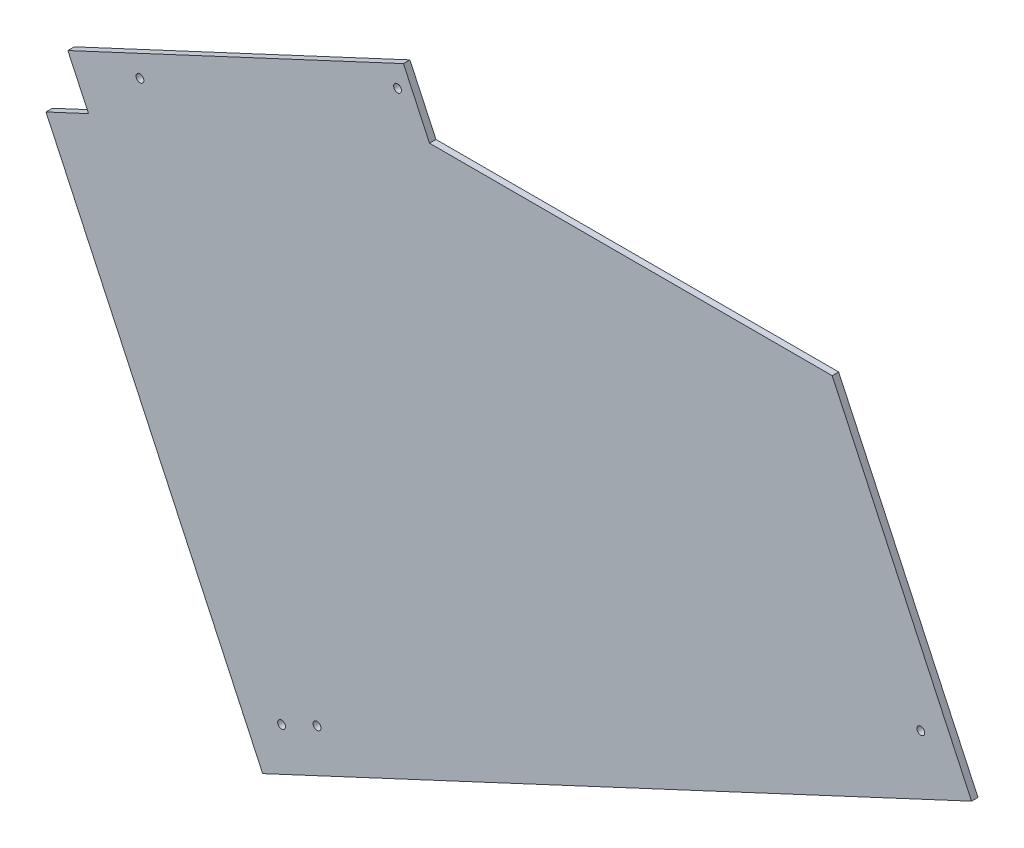
SolidWorks part; units mm, degrees
ref_plane "Front Plane" through (0, 0, 0) normal (0, 0, 1) x (1, 0, 0)
ref_plane "Top Plane" through (0, 0, 0) normal (0, 1, 0) x (1, 0, 0)
ref_plane "Right Plane" through (0, 0, 0) normal (1, 0, 0) x (0, 0, -1)
sketch "Sketch1" plane through (0, 0, 0) normal (0, 0, 1) x (1, 0, 0)
  line L0 (327.4362, 0.0035) -> (121.4984, 0.0035)
  line L1 (121.4984, 0.0035) -> (108.169, 28.5884)
  line L2 (108.169, 28.5884) -> (-63.4467, -51.4373)
  line L3 (-63.4467, -51.4373) -> (57.9293, -311.7289) construction
  line L4 (57.9293, -311.7289) -> (398.701, -152.8244)
  line L5 (271.5352, 119.8836) -> (277.3251, 107.4672) construction
  line L6 (190.5834, 136.311) -> (-12.0446, 41.824) construction
  line L7 (-63.4467, -51.4373) -> (255.5737, 97.3243) construction
  line L8 (398.701, -152.8244) -> (327.4362, 0.0035)
  line L9 (57.9293, -311.7289) -> (36.1779, -321.8717)
  line L10 (36.1779, -321.8717) -> (-74.6326, -84.2378)
  line L11 (50.7481, 0) -> (323.7481, 0) construction
  line L12 (-74.6326, -84.2378) -> (-52.8812, -74.095)
  line L13 (-90.9879, -49.1637) -> (-85.1981, -61.5801) construction
  line L14 (-52.8812, -74.095) -> (-63.4467, -51.4373)
  circle A0 centre (162.7613, -40.6644) radius 32.5 construction
  circle A1 centre (336.0773, -108.8767) radius 32.5 construction
  circle A2 centre (90.1802, -40.6644) radius 32.5 construction
  circle A3 centre (232.5481, -40.6644) radius 32.5 construction
  circle A4 centre (207.2768, 100.5118) radius 39.5 construction
  arc A5 (-3.3339, 41.4724) -> (-17.3744, 34.9252) centre (-8.0297, 33.2141) ccw construction
  circle A6 centre (304.5287, -40.6644) radius 32.5 construction
  circle A7 centre (254.9584, -108.8767) radius 32.5 construction
  circle A8 centre (179.3206, -108.8767) radius 32.5 construction
  circle A9 centre (101.4264, -108.8767) radius 32.5 construction
  circle A10 centre (270.383, -163.8108) radius 32.5 construction
  circle A11 centre (372.7594, -134.5783) radius 2
  dimension "D2" = 65
  dimension "D3" = 65
  dimension "D5" = 4
  dimension "D1" = 350
  dimension "D4" = 25
  dimension "24.5/2" = 15.8
  dimension "D6" = 27.5
extrude "Boss-Extrude1" add sketch "Sketch1" along normal up to surface (3.3 mm away)
sketch "Sketch2" plane through (0, 0, 3.3) normal (0, 0, 1) x (1, 0, 0)
  circle A0 centre (105.1447, 16.1444) radius 2
  circle A1 centre (-26.5934, -45.2861) radius 2
  circle A2 centre (-26.5934, -45.2861) radius 2 construction
  circle A3 centre (105.1447, 16.1444) radius 2 construction
extrude "Cut-Extrude1" cut sketch "Sketch2" against normal through all
sketch "Sketch3" plane through (0, 0, 3.3) normal (0, 0, 1) x (1, 0, 0)
  line L2 (398.701, -152.8244) -> (36.1779, -321.8717) construction
  line L3 (36.1779, -321.8717) -> (-74.6326, -84.2378) construction
  circle A0 centre (45.8517, -295.2932) radius 2
  circle A1 centre (63.9779, -286.8408) radius 2
  dimension "D1" = 4
  dimension "D2" = 4
  dimension "D3" = 20
  dimension "D5" = 20
  dimension "D6" = 20
  dimension "D4" = 20
extrude "Cut-Extrude2" cut sketch "Sketch3" against normal blind 4
